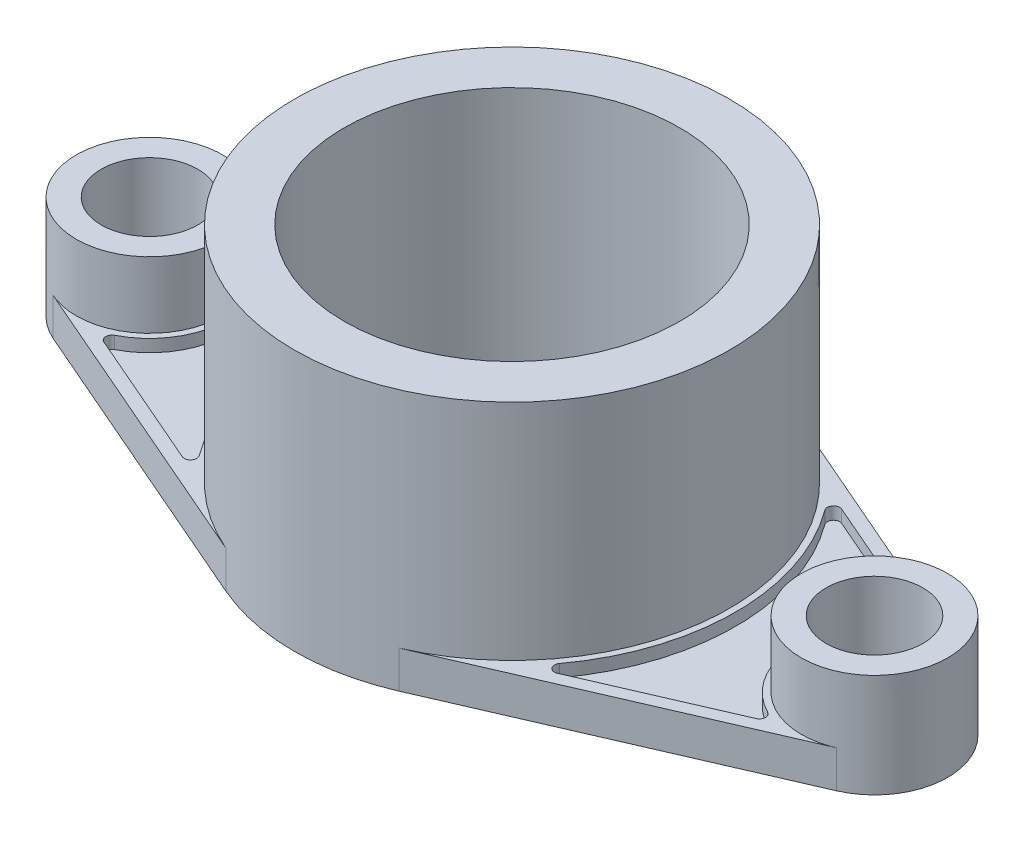
SolidWorks part; units mm, degrees
ref_plane "Front Plane" through (0, 0, 0) normal (0, 0, 1) x (1, 0, 0)
ref_plane "Top Plane" through (0, 0, 0) normal (0, 1, 0) x (1, 0, 0)
ref_plane "Right Plane" through (0, 0, 0) normal (1, 0, 0) x (0, 0, -1)
sketch "Sketch1" plane through (0, 0, 0) normal (0, 1, 0) x (1, 0, 0)
  circle A0 centre (0, 0) radius 52.5
  circle A1 centre (0, 0) radius 40.5
  dimension "D1" = 105
  dimension "D2" = 81
extrude "Boss-Extrude1" add sketch "Sketch1" along normal blind 63
ref_plane "Plane1" through (0, 25, 0) normal (0, 1, 0) x (1, 0, 0)
sketch "Sketch2" plane through (0, 25, 0) normal (0, 1, 0) x (1, 0, 0)
  circle A0 centre (87.5, 0) radius 17.665
  circle A1 centre (87.5, 0) radius 11.665
  circle A2 centre (-87.5, 0) radius 17.665
  circle A3 centre (-87.5, 0) radius 11.665
  dimension "D1" = 23.33
  dimension "D2" = 35.33
  dimension "D3" = 23.33
  dimension "D4" = 35.33
  dimension "D5" = 175
extrude "Boss-Extrude2" add sketch "Sketch2" against normal blind 25 separate body
ref_plane "Plane2" through (0, 0, 0) normal (0, -1, 0) x (-1, 0, 0)
sketch "Sketch3" plane through (0, 0, 0) normal (0, -1, 0) x (-1, 0, 0)
  line L0 (-94.5327, 16.2047) -> (-20.901, 48.1601)
  line L1 (20.901, 48.1601) -> (94.5327, 16.2047)
  line L2 (94.5327, -16.2047) -> (20.901, -48.1601)
  line L3 (-94.5327, -16.2047) -> (-20.901, -48.1601)
  circle A0 centre (0, 0) radius 52.5 construction
  circle A1 centre (-87.5, 0) radius 17.665 construction
  circle A2 centre (87.5, 0) radius 17.665 construction
  arc A3 (-20.901, 48.1601) -> (-20.901, -48.1601) centre (0, 0) ccw
  arc A4 (-94.5327, -16.2047) -> (-94.5327, 16.2047) centre (-87.5, 0) ccw
  arc A5 (94.5327, 16.2047) -> (94.5327, -16.2047) centre (87.5, 0) ccw
  arc A6 (20.901, -48.1601) -> (20.901, 48.1601) centre (0, 0) ccw
extrude "Boss-Extrude3" add sketch "Sketch3" against normal blind 9
sketch "Sketch4" plane through (0, 63, 0) normal (0, 1, 0) x (1, 0, 0)
  line L0 (0, -34.65) -> (0, 34.65) construction
  line L1 (-78.7263, 19.7942) -> (-45.2648, 34.3162)
  line L2 (-94.5327, 16.2047) -> (-20.901, 48.1601) construction
  line L3 (-34.65, 0) -> (34.65, 0) construction
  line L4 (-78.7263, -19.7942) -> (-45.2648, -34.3162)
  line L5 (78.7263, -19.7942) -> (45.2648, -34.3162)
  line L6 (78.7263, 19.7942) -> (45.2648, 34.3162)
  arc A0 (43.4604, -32.0499) -> (43.4604, 32.0499) centre (0, 0) ccw
  arc A2 (-78.8094, -17.0813) -> (-78.8094, 17.0813) centre (-87.5, 0) ccw
  arc A3 (78.8094, -17.0813) -> (78.8094, 17.0813) centre (87.5, 0) cw
  arc A4 (-78.7263, 19.7942) -> (-78.8094, 17.0813) centre (-78.1292, 18.4182) ccw
  arc A5 (-43.4604, 32.0499) -> (-45.2648, 34.3162) centre (-44.6676, 32.9402) ccw
  arc A6 (-43.4604, -32.0499) -> (-45.2648, -34.3162) centre (-44.6676, -32.9402) cw
  arc A7 (-78.7263, -19.7942) -> (-78.8094, -17.0813) centre (-78.1292, -18.4182) cw
  arc A8 (43.4604, -32.0499) -> (45.2648, -34.3162) centre (44.6676, -32.9402) ccw
  arc A9 (78.7263, -19.7942) -> (78.8094, -17.0813) centre (78.1292, -18.4182) ccw
  arc A10 (43.4604, 32.0499) -> (45.2648, 34.3162) centre (44.6676, 32.9402) cw
  arc A11 (78.7263, 19.7942) -> (78.8094, 17.0813) centre (78.1292, 18.4182) cw
  arc A12 (-43.4604, 32.0499) -> (-43.4604, -32.0499) centre (0, 0) ccw
  dimension "D1" = 108
  dimension "D2" = 38.33
  dimension "D4" = 3
  dimension "D5" = 3
  dimension "D3" = 3
extrude "Cut-Extrude1" cut sketch "Sketch4" against normal blind 57
